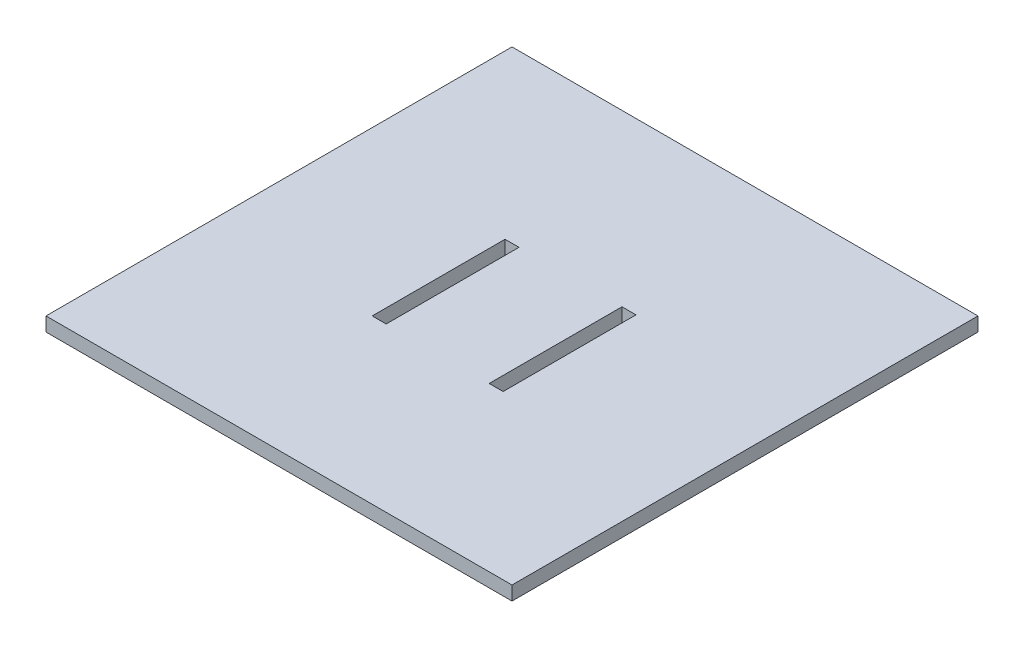
SolidWorks part; units mm, degrees
ref_plane "Plano frontal" through (0, 0, 0) normal (0, 0, 1) x (1, 0, 0)
ref_plane "Plano superior" through (0, 0, 0) normal (0, 1, 0) x (1, 0, 0)
ref_plane "Plano direito" through (0, 0, 0) normal (1, 0, 0) x (0, 0, -1)
sketch "BaixoBaseEsb" plane through (0, 0, 0) normal (0, 1, 0) x (1, 0, 0)
  line L1 (0, 0) -> (100, 0)
  line L2 (0, 0) -> (0, 100)
  line L3 (0, 100) -> (100, 100)
  line L4 (100, 0) -> (100, 100)
  line L5 (35, 63.5) -> (38, 63.5)
  line L6 (35, 63.5) -> (35, 35)
  line L7 (35, 35) -> (38, 35)
  line L8 (38, 63.5) -> (38, 35)
  line L9 (60.1, 63.5) -> (63.1, 63.5)
  line L10 (60.1, 63.5) -> (60.1, 35)
  line L11 (60.1, 35) -> (63.1, 35)
  line L12 (63.1, 63.5) -> (63.1, 35)
  dimension "D1" = 100
  dimension "D2" = 100
  dimension "D3" = 28.5
  dimension "D4" = 3
  dimension "D5" = 22.1
  dimension "D6" = 3
  dimension "D7" = 35
  dimension "D8" = 35
extrude "Ressalto-extrusão1" add sketch "BaixoBaseEsb" along normal blind 3
